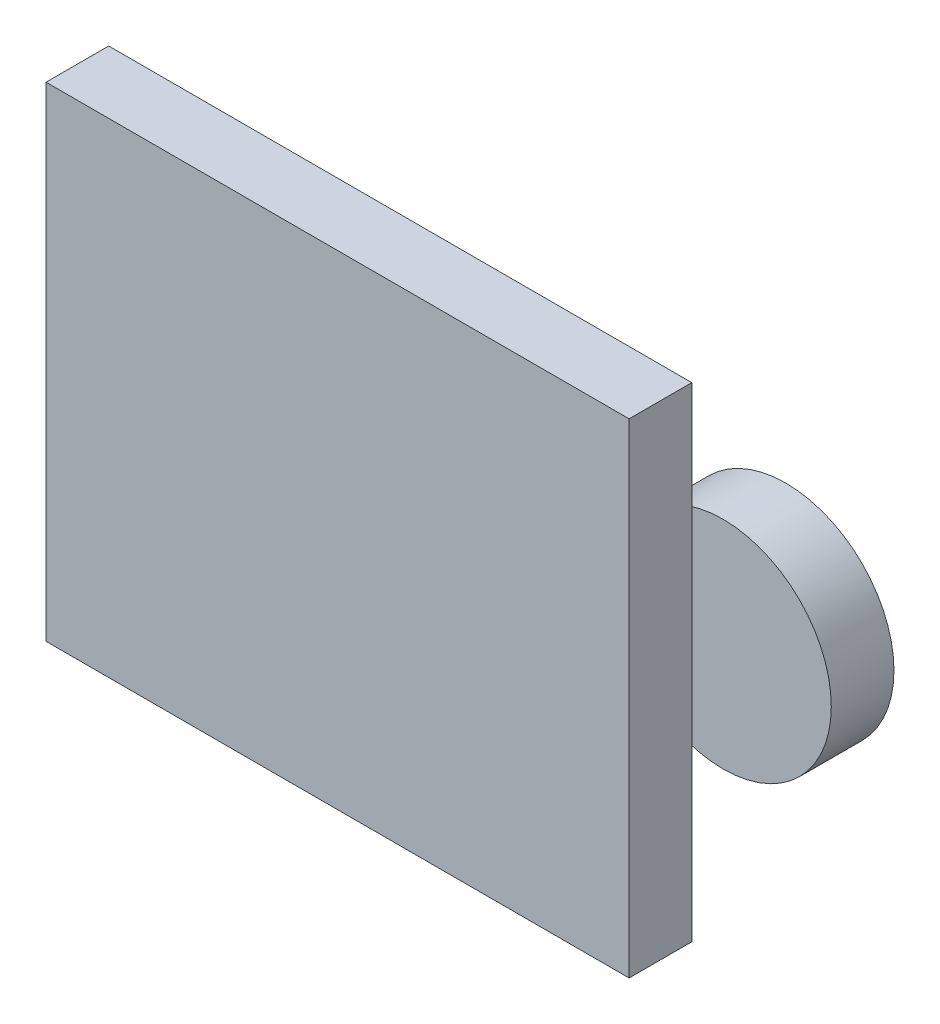
SolidWorks part; units mm, degrees
ref_plane "Спереди" through (0, 0, 0) normal (0, 0, 1) x (1, 0, 0)
ref_plane "Сверху" through (0, 0, 0) normal (0, 1, 0) x (1, 0, 0)
ref_plane "Справа" through (0, 0, 0) normal (1, 0, 0) x (0, 0, -1)
sketch "Эскиз1_fr" plane through (0, 0, 0) normal (0, 0, 1) x (1, 0, 0)
  line L1 (-48.994, 38.0205) -> (44.0482, 38.0205)
  line L2 (-48.994, 38.0205) -> (-48.994, -39.257)
  line L3 (-48.994, -39.257) -> (44.0482, -39.257)
  line L4 (44.0482, 38.0205) -> (44.0482, -39.257)
extrude "Бобышка-Вытянуть1" add sketch "Эскиз1_fr" along normal blind 10
ref_plane "Плоскость4" through (0, 0, -5) normal (0, 0, 1) x (1, 0, 0)
sketch "Эскиз5" plane through (0, 0, -5) normal (0, 0, 1) x (1, 0, 0)
  line L0 (44.0482, -39.257) -> (44.0482, 38.0205) construction
  circle A0 centre (44.0482, -0.6182) radius 17.2618
extrude "Бобышка-Вытянуть2" add sketch "Эскиз5" against normal blind 10 separate body
